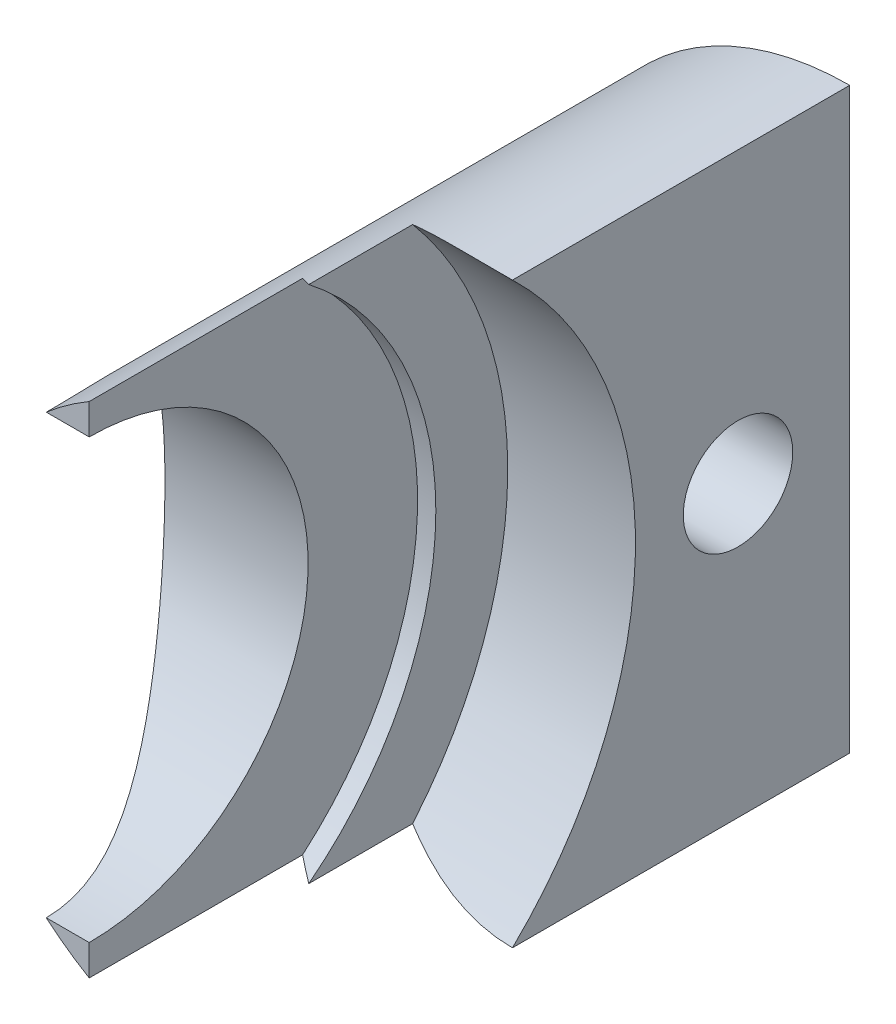
SolidWorks part; units mm, degrees
ref_plane "Front" through (0, 0, 0) normal (0, 0, 1) x (1, 0, 0)
ref_plane "Top" through (0, 0, 0) normal (0, 1, 0) x (1, 0, 0)
ref_plane "Right" through (0, 0, 0) normal (1, 0, 0) x (0, 0, -1)
sketch "Sketch1" plane through (0, 0, 0) normal (0, 0, 1) x (1, 0, 0)
  circle A0 centre (0, 0) radius 7.925
extrude "Extrude1" add sketch "Sketch1" along normal blind 16.8438
sketch "Sketch2" plane through (0, 0, 0) normal (0, 1, 0) x (1, 0, 0)
  line L2 (0, 0) -> (7.925, 0)
  line L4 (0, 0) -> (0, -17)
  line L7 (0, -17) -> (7.925, -17)
  line L8 (7.925, 0) -> (7.925, -17)
extrude "Cut-Extrude1" cut sketch "Sketch2" against normal through all and the other way through all
sketch "Sketch3" plane through (0, 0, 0) normal (1, 0, 0) x (0, 0, -1)
  line L0 (-16.8438, 0) -> (0, 0) construction
  circle A0 centre (-16.8731, 0) radius 11
extrude "Cut-Extrude2" cut sketch "Sketch3" against normal blind 3.5
sketch "Sketch6" plane through (0, 0, 0) normal (1, 0, 0) x (0, 0, -1)
  line L0 (-16.8438, 0) -> (0, 0) construction
  circle A0 centre (-16.8438, 0) radius 9
extrude "Cut-Extrude5" cut sketch "Sketch6" against normal blind 4
sketch "Sketch7" plane through (0, 0, 0) normal (1, 0, 0) x (0, 0, -1)
  line L0 (-16.8438, 0) -> (0, 0) construction
  circle A0 centre (-16.8438, 0) radius 6
  circle A1 centre (-3.0625, 0) radius 1.5
extrude "Cut-Extrude6" cut sketch "Sketch7" against normal through all
